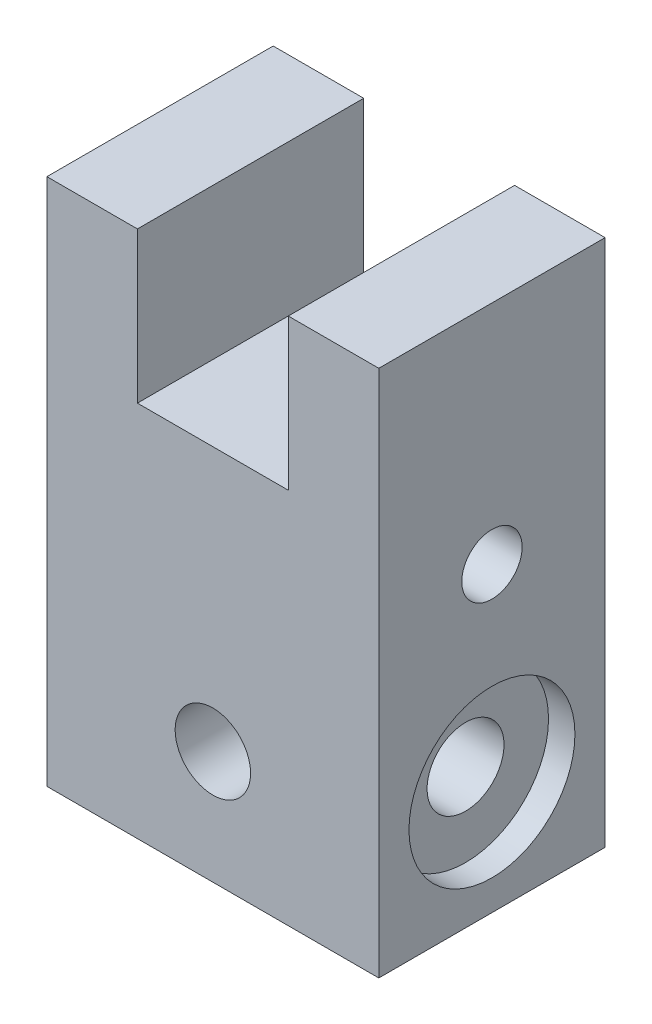
SolidWorks part; units mm, degrees
ref_plane "Alzado" through (0, 0, 0) normal (0, 0, 1) x (1, 0, 0)
ref_plane "Planta" through (0, 0, 0) normal (0, 1, 0) x (1, 0, 0)
ref_plane "Vista lateral" through (0, 0, 0) normal (1, 0, 0) x (0, 0, -1)
sketch "Croquis1" plane through (0, 0, 0) normal (0, 0, 1) x (1, 0, 0)
  line L0 (0, 25) -> (0, 0) construction
  line L1 (-22, 35) -> (22, 35)
  line L2 (-22, 35) -> (-22, -35)
  line L3 (-22, -35) -> (22, -35)
  line L4 (22, 35) -> (22, -35)
  line L5 (-22, 35) -> (22, -35) construction
  line L6 (-22, -35) -> (22, 35) construction
  line L7 (0, 0) -> (0, -20) construction
  line L8 (-10, 15) -> (10, 15)
  line L9 (-10, 15) -> (-10, 35)
  line L10 (-10, 35) -> (10, 35)
  line L11 (10, 15) -> (10, 35)
  line L12 (-10, 15) -> (10, 35) construction
  line L13 (-10, 35) -> (10, 15) construction
  circle A0 centre (0, -20) radius 5
  point P0 (0, 0)
  point P8 (0, 25)
  dimension "D4" = 10
  dimension "D1" = 20
  dimension "D2" = 20
  dimension "D3" = 50
  dimension "D5" = 20
  dimension "D6" = 44
extrude "Saliente-Extruir1" add sketch "Croquis1" along normal blind 30 contours L11 L8 L9 L1 L2 L3 L4 A0
sketch "Croquis2" plane through (22, 0, 0) normal (1, 0, 0) x (0, 0, -1)
  line L0 (-15, -35) -> (-15, -20) construction
  line L1 (-30, -35) -> (0, -35) construction
  circle A0 centre (-15, -20) radius 11
  dimension "D1" = 22
  dimension "D2" = 20
extrude "Cortar-Extruir1" cut sketch "Croquis2" against normal blind 3.5
sketch "Croquis3" plane through (18.5, 0, 0) normal (1, 0, 0) x (0, 0, -1)
  line L0 (-15, -35) -> (-15, -20) construction
  line L1 (-30, -35) -> (0, -35) construction
  circle A0 centre (-15, -20) radius 5.1
  dimension "D1" = 10.2
extrude "Cortar-Extruir2" cut sketch "Croquis3" against normal through all
sketch "Croquis4" plane through (22, 0, 0) normal (1, 0, 0) x (0, 0, -1)
  line L0 (-15, 35) -> (-15, 15) construction
  line L1 (-30, 35) -> (0, 35) construction
  line L2 (-15, 15) -> (-15, 5) construction
  circle A0 centre (-15, 5) radius 4
  dimension "D2" = 8
  dimension "D1" = 20
  dimension "D3" = 10
extrude "Cortar-Extruir3" cut sketch "Croquis4" against normal through all
